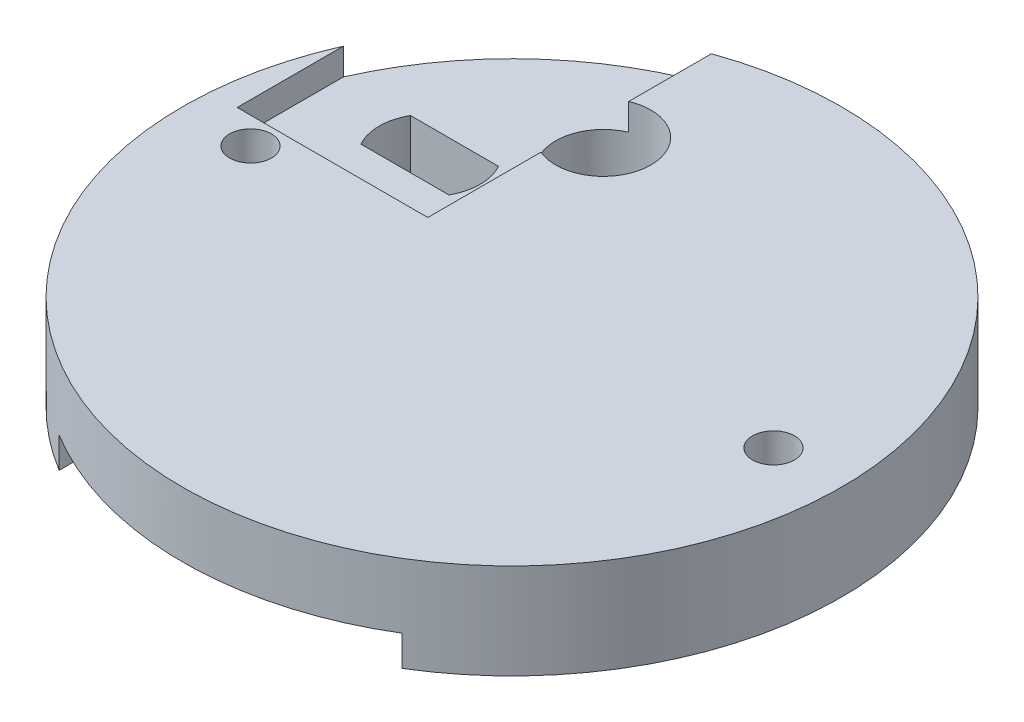
SolidWorks part; units mm, degrees
ref_plane "前视基准面" through (0, 0, 0) normal (0, 0, 1) x (1, 0, 0)
ref_plane "上视基准面" through (0, 0, 0) normal (0, 1, 0) x (1, 0, 0)
ref_plane "右视基准面" through (0, 0, 0) normal (1, 0, 0) x (0, 0, -1)
sketch "草图1" plane through (0, 0, 0) normal (0, 1, 0) x (1, 0, 0)
  line L0 (0, 0) -> (-27.1848, 0) construction
  line L1 (0, 0) -> (0, -9.0346) construction
  line L2 (-12.3092, 6.98) -> (-7.6908, 6.98)
  line L3 (-12.3092, 4.38) -> (-7.6908, 4.38)
  line L4 (12.3092, 6.98) -> (7.6908, 6.98)
  line L5 (12.3092, 4.38) -> (7.6908, 4.38)
  circle A0 centre (0, 0) radius 17.29
  circle A1 centre (-13.72, 0) radius 1.1
  circle A2 centre (13.72, 0) radius 1.1
  circle A3 centre (-4.85, 9.64) radius 2.5
  arc A5 (-12.3092, 6.98) -> (-12.3092, 4.38) centre (-10, 5.68) ccw
  arc A8 (-7.6908, 4.38) -> (-7.6908, 6.98) centre (-10, 5.68) ccw
  arc A9 (12.3092, 6.98) -> (12.3092, 4.38) centre (10, 5.68) cw
  arc A10 (7.6908, 4.38) -> (7.6908, 6.98) centre (10, 5.68) cw
  dimension "D1" = 34.58
  dimension "D2" = 13.72
  dimension "D4" = 2.2
  dimension "D5" = 2.2
  dimension "D6" = 4.85
  dimension "D8" = 5
  dimension "D9" = 5.3
  dimension "D10" = 2.6
  dimension "D3" = 13.72
  dimension "D7" = 9.64
  dimension "D11" = 10
  dimension "D12" = 5.68
  dimension "D13" = 1.3
extrude "凸台-拉伸1" add sketch "草图1" along normal blind 4
sketch "草图2" plane through (0, 0, 0) normal (0, -1, 0) x (1, 0, 0)
  line L0 (0, 0) -> (20.6825, 0) construction
  line L1 (-9.22, 3.3) -> (-5.22, 3.3)
  line L2 (-9.22, 3.3) -> (-9.22, -1.5)
  line L3 (-9.22, -1.5) -> (-5.22, -1.5)
  line L4 (-5.22, 3.3) -> (-5.22, -1.5)
  line L5 (0, 0.7878) -> (0, -6.0913) construction
  line L6 (6, 0.6) -> (10, 0.6)
  line L7 (6, 0.6) -> (6, -2.8)
  line L8 (6, -2.8) -> (10, -2.8)
  line L9 (10, 0.6) -> (10, -2.8)
  line L10 (-17.196, 5.8) -> (-12.796, 5.8)
  line L11 (-17.196, 5.8) -> (-17.196, 1.8)
  line L12 (-17.196, 1.8) -> (-12.796, 1.8)
  line L13 (-12.796, 5.8) -> (-12.796, 1.8)
  line L19 (-9, 5.29) -> (9, 5.29)
  line L20 (-9, 5.29) -> (-9, 17.29)
  line L21 (-9, 17.29) -> (9, 17.29)
  line L22 (9, 5.29) -> (9, 17.29)
  line L23 (-9, 5.29) -> (9, 17.29) construction
  line L24 (-9, 17.29) -> (9, 5.29) construction
  circle A0 centre (-13.72, 0) radius 1.1 construction
  circle A1 centre (0, 0) radius 17.29 construction
  point P22 (0, 11.29)
  dimension "D3" = 4.5
  dimension "D5" = 3.4
  dimension "D1" = 4
  dimension "D2" = 4.8
  dimension "D4" = 1.5
  dimension "D6" = 4
  dimension "D7" = 6
  dimension "D8" = 2.8
  dimension "D9" = 4
  dimension "D10" = 1.8
  dimension "D11" = 4.4
  dimension "D12" = 12
  dimension "D13" = 18
extrude "切除-拉伸1" cut sketch "草图2" against normal blind 1.6
sketch "草图3" plane through (0, 4, 0) normal (0, 1, 0) x (1, 0, 0)
  circle A0 centre (0, 0) radius 17.29 construction
  circle A1 centre (0, 0) radius 17.29
  circle A2 centre (-4.85, 9.64) radius 2.5 construction
  circle A3 centre (-4.85, 9.64) radius 2.5
  circle A4 centre (-13.72, 0) radius 1.1 construction
  circle A5 centre (-13.72, 0) radius 1.1
  circle A6 centre (13.72, 0) radius 1.1 construction
  circle A7 centre (13.72, 0) radius 1.1
extrude "凸台-拉伸2" add sketch "草图3" along normal blind 1
sketch "草图4" plane through (0, 5, 0) normal (0, 1, 0) x (1, 0, 0)
  line L0 (0, 0) -> (6.0206, 0) construction
  line L1 (-15.82, 16.4) -> (-5.82, 16.4)
  line L2 (-15.82, 16.4) -> (-15.82, 1.4)
  line L3 (-15.82, 1.4) -> (-5.82, 1.4)
  line L4 (-5.82, 16.4) -> (-5.82, 1.4)
  line L5 (0, 0) -> (0, -7.8731) construction
  circle A1 centre (-13.72, 0) radius 1.1 construction
  circle A2 centre (-13.72, 0) radius 1.1 construction
  circle A3 centre (-13.72, 0) radius 2.1 construction
  dimension "D3" = 1
  dimension "D1" = 10
  dimension "D2" = 15
  dimension "D4" = 1.4
extrude "切除-拉伸2" cut sketch "草图4" against normal blind 1.4
